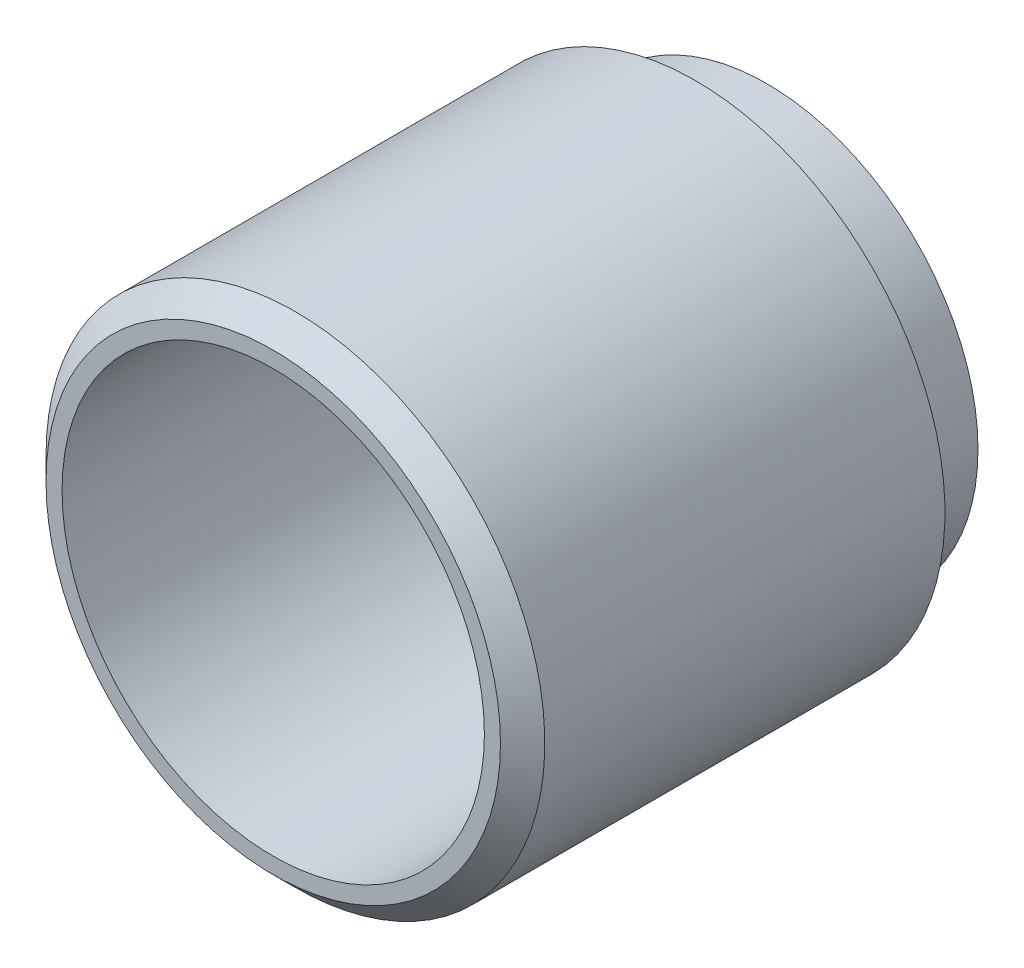
SolidWorks part; units mm, degrees
ref_plane "Front Plane" through (0, 0, 0) normal (0, 0, 1) x (1, 0, 0)
ref_plane "Top Plane" through (0, 0, 0) normal (0, 1, 0) x (1, 0, 0)
ref_plane "Right Plane" through (0, 0, 0) normal (1, 0, 0) x (0, 0, -1)
sketch "Sketch1" plane through (0, 0, 0) normal (0, 0, 1) x (1, 0, 0)
  circle A0 centre (-70, 40) radius 22.5
  circle A1 centre (-70, 40) radius 19.05
  circle A2 centre (-70, 40) radius 19.05 construction
  dimension "D1" = 45
extrude "Boss-Extrude1" add sketch "Sketch1" along normal blind 38.1
sketch "Sketch2" plane through (0, 0, 0) normal (0, 0, 1) x (1, 0, 0)
  circle A0 centre (-70, 40) radius 19.05
  circle A1 centre (-70, 40) radius 15.875
  circle A2 centre (-70, 40) radius 19.05 construction
  dimension "D1" = 3.175
extrude "Boss-Extrude2" add sketch "Sketch2" against normal blind 6.4314 separate body
chamfer "Chamfer1" distance 2 angle 45 1 edges at (-47.5, 40, 38.1)
